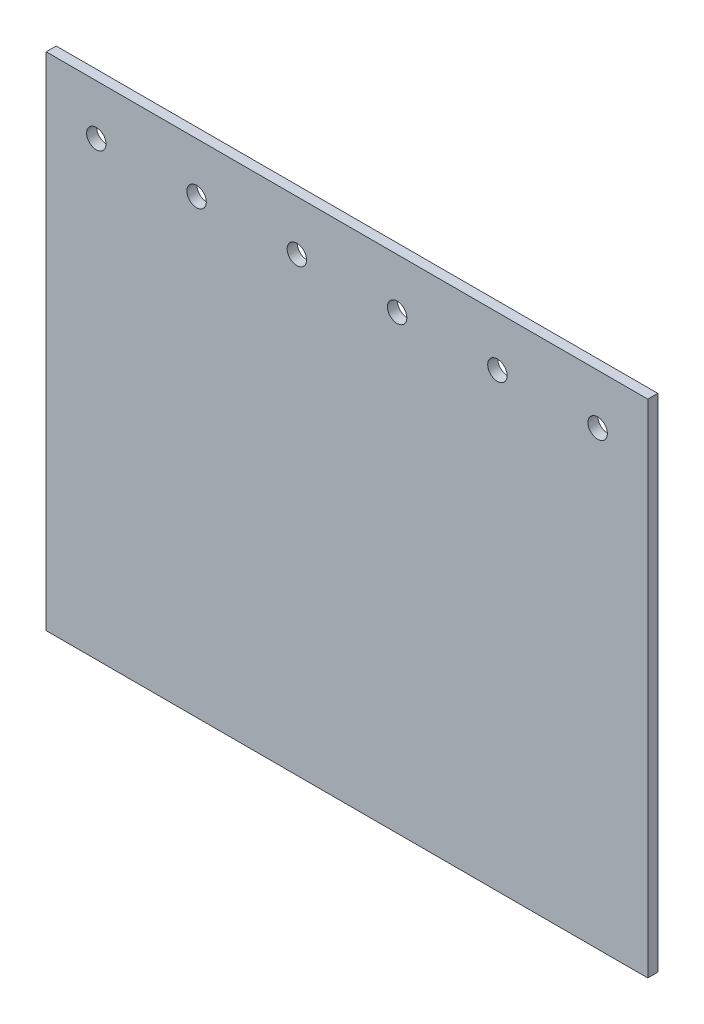
SolidWorks part; units mm, degrees
material "ABS"
ref_plane "Front Plane" through (0, 0, 0) normal (0, 0, 1) x (1, 0, 0)
ref_plane "Top Plane" through (0, 0, 0) normal (0, 1, 0) x (1, 0, 0)
ref_plane "Right Plane" through (0, 0, 0) normal (1, 0, 0) x (0, 0, -1)
sketch "Sketch1" plane through (0, 0, 0) normal (0, 0, 1) x (1, 0, 0)
  line L1 (0, 0) -> (-152.4, 0)
  line L2 (0, 0) -> (0, 127)
  line L3 (0, 127) -> (-152.4, 127)
  line L4 (-152.4, 0) -> (-152.4, 127)
  dimension "D1" = 127
  dimension "D2" = 152.4
extrude "Boss-Extrude1" add sketch "Sketch1" along normal blind 2.54
hole_wizard "#10 (0.1935) Diameter Hole1" positions "Sketch3" profile "Sketch4" hole size "#10" standard "ANSI Inch" end condition through all
sketch "Sketch3" plane through (0, 0, 2.54) normal (0, 0, 1) x (1, 0, 0)
  line L0 (0, 127) -> (-152.4, 127) construction
  line L1 (-152.4, 127) -> (-152.4, 0) construction
  point P0 (-139.7, 114.3)
  point P2 (-114.3, 114.3)
  point P4 (-88.9, 114.3)
  point P6 (-63.5, 114.3)
  point P8 (-38.1, 114.3)
  point P14 (-12.7, 114.3)
  dimension "D1" = 12.7
  dimension "D2" = 25.4
  dimension "D3" = 25.4
  dimension "D4" = 25.4
  dimension "D5" = 25.4
  dimension "D6" = 25.4
  dimension "D7" = 12.7
sketch "Sketch4" plane through (-139.7, 114.3, 2.54) normal (1, 0, 0) x (0, -1, 0)
  line L0 (0, 0) -> (0, 2.54)
  line L1 (0, 2.54) -> (2.4574, 2.54)
  line L2 (2.4574, 2.54) -> (2.4574, 0)
  line L5 (2.4574, 0) -> (0, 0)
  line L11 (0, -6.35) -> (0, 107.95) construction
  dimension "Thru Hole Dia." = 4.9149
  dimension "Thru Hole Depth" = 2.54
